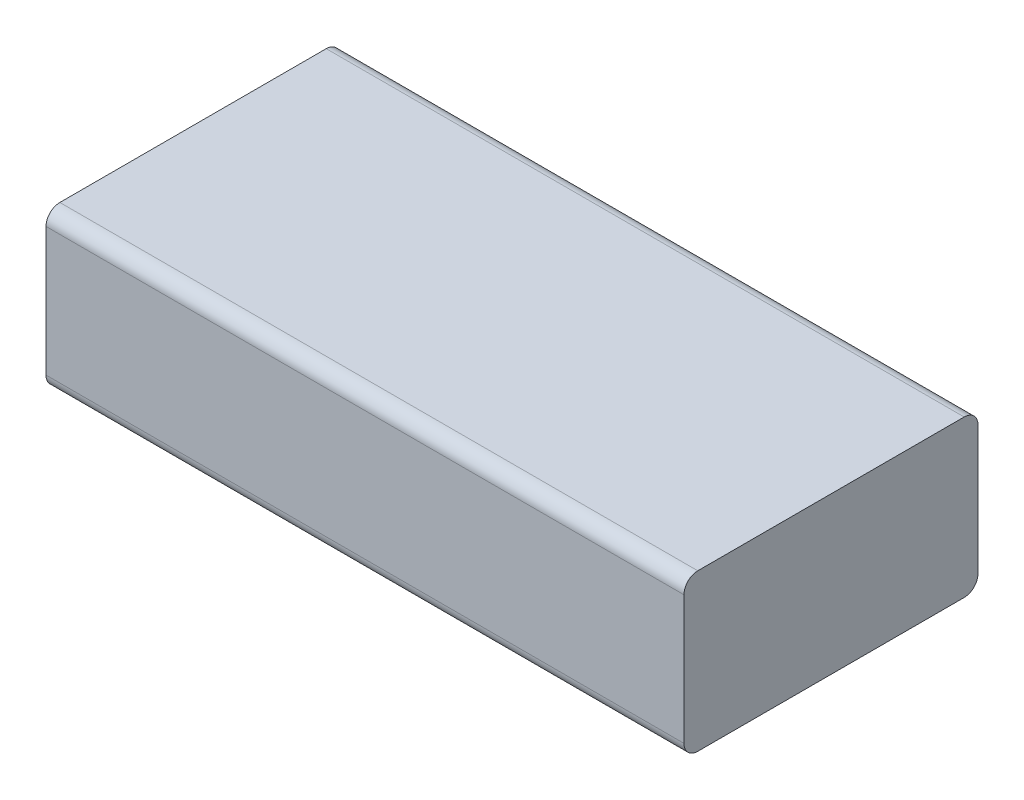
SolidWorks part; units mm, degrees
ref_plane "前视基准面" through (0, 0, 0) normal (0, 0, 1) x (1, 0, 0)
ref_plane "上视基准面" through (0, 0, 0) normal (0, 1, 0) x (1, 0, 0)
ref_plane "右视基准面" through (0, 0, 0) normal (1, 0, 0) x (0, 0, -1)
sketch "草图1" plane through (0, 0, 0) normal (0, 1, 0) x (1, 0, 0)
  line L1 (-46.1, -21.25) -> (46.1, -21.25)
  line L2 (-46.1, -21.25) -> (-46.1, 21.25)
  line L3 (-46.1, 21.25) -> (46.1, 21.25)
  line L4 (46.1, -21.25) -> (46.1, 21.25)
  line L5 (-46.1, -21.25) -> (46.1, 21.25) construction
  line L6 (-46.1, 21.25) -> (46.1, -21.25) construction
  point P0 (0, 0)
  dimension "D1" = 92.2
  dimension "D2" = 42.5
extrude "凸台-拉伸1" add sketch "草图1" along normal blind 22.6
fillet "圆角1" radius 2 4 edges at (0, 0, -21.25) (0, 0, 21.25) (0, 22.6, -21.25) (0, 22.6, 21.25)
sketch "草图6" plane through (-46.1, 0, 0) normal (-1, 0, 0) x (0, 0, 1)
  line L0 (-21.25, 20.6) -> (-21.25, 2) construction
  line L1 (0, 11.6) -> (15, 11.6)
  line L2 (0, 11.6) -> (0, 17.6)
  line L3 (0, 17.6) -> (15, 17.6)
  line L4 (15, 11.6) -> (15, 17.6)
  line L5 (-19.25, 0) -> (19.25, 0) construction
  line L6 (-19.25, 22.6) -> (19.25, 22.6) construction
  circle A0 centre (-16, 4) radius 1.5
  dimension "D1" = 3
  dimension "D2" = 5.25
  dimension "D3" = 4
  dimension "D4" = 16
  dimension "D5" = 15
  dimension "D6" = 6
  dimension "D7" = 5
extrude "凸台-拉伸5" add sketch "草图6" along normal blind 3 contours A0 | L1 L4 L3 L2
